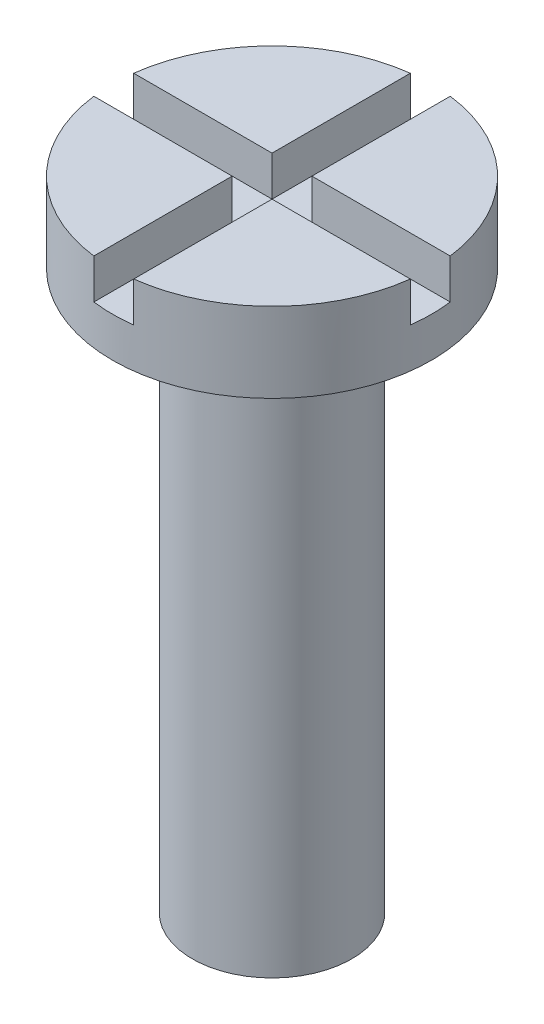
SolidWorks part; units mm, degrees
material "PTFE (general)"
ref_plane "Front Plane" through (0, 0, 0) normal (0, 0, 1) x (1, 0, 0)
ref_plane "Top Plane" through (0, 0, 0) normal (0, 1, 0) x (1, 0, 0)
ref_plane "Right Plane" through (0, 0, 0) normal (1, 0, 0) x (0, 0, -1)
sketch "Sketch1" plane through (0, 0, 0) normal (0, 1, 0) x (1, 0, 0)
  circle A0 centre (0, 0) radius 1
extrude "Boss-Extrude1" add sketch "Sketch1" along normal blind 7
sketch "Sketch2" plane through (0, 7, 0) normal (0, 1, 0) x (1, 0, 0)
  circle A0 centre (0, 0) radius 2
extrude "Boss-Extrude2" add sketch "Sketch2" along normal blind 1
sketch "Sketch3" plane through (0, 8, 0) normal (0, 1, 0) x (1, 0, 0)
  line L0 (-2, 0.25) -> (-2, -0.25)
  line L1 (-0.25, -2) -> (0.25, -2)
  line L2 (-2, -0.25) -> (-0.25, -0.25)
  line L3 (-2, 0.25) -> (-0.25, 0.25)
  line L4 (-0.25, 2) -> (-0.25, 0.25)
  line L5 (0.25, 2) -> (0.25, 0.25)
  line L6 (2, -0.25) -> (2, 0.25)
  line L7 (0.25, 0.25) -> (2, 0.25)
  line L8 (-0.25, 2) -> (0.25, 2)
  line L11 (0.25, -0.25) -> (2, -0.25)
  line L13 (0.25, -0.25) -> (0.25, -2)
  line L15 (-0.25, -0.25) -> (-0.25, -2)
extrude "Cut-Extrude1" cut sketch "Sketch3" against normal blind 0.5
